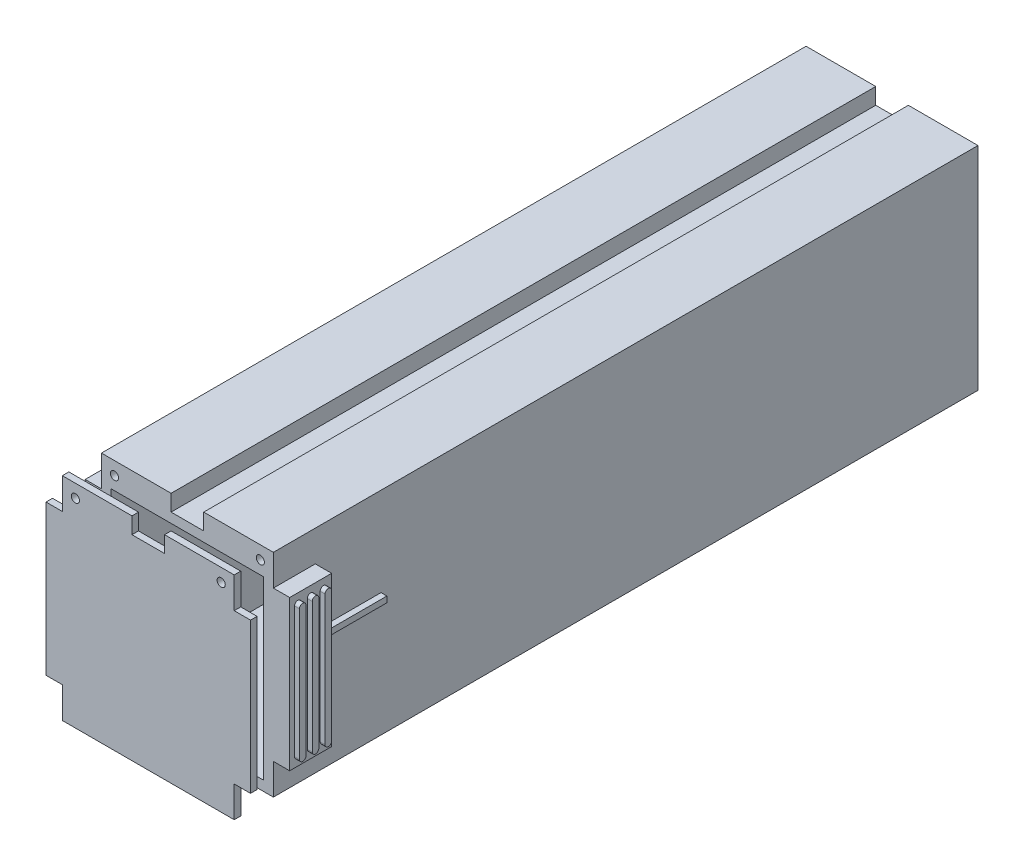
SolidWorks part; units mm, degrees
ref_plane "前视基准面" through (0, 0, 0) normal (0, 0, 1) x (1, 0, 0)
ref_plane "上视基准面" through (0, 0, 0) normal (0, 1, 0) x (1, 0, 0)
ref_plane "右视基准面" through (0, 0, 0) normal (1, 0, 0) x (0, 0, -1)
other "Configuration Table"
sketch "草图1" plane through (0, 0, 0) normal (0, 0, 1) x (1, 0, 0)
  line L1 (0, 0) -> (52.7, 0)
  line L2 (0, 0) -> (0, 65)
  line L3 (0, 65) -> (52.7, 65)
  line L4 (52.7, 0) -> (52.7, 65)
  line L5 (0, 0) -> (52.7, 65) construction
  line L6 (0, 65) -> (52.7, 0) construction
  point P4 (26.35, 32.5)
  dimension "D1" = 52.7
  dimension "D2" = 65
extrude "凸台-拉伸1" add sketch "草图1" along normal blind 216
sketch "草图2" plane through (0, 0, 216) normal (0, 0, 1) x (1, 0, 0)
  line L0 (26.35, 65) -> (26.35, 0) construction
  line L2 (21.35, 65) -> (31.35, 65)
  line L3 (21.35, 65) -> (21.35, 60)
  line L4 (0, 65) -> (0, 0)
  line L5 (0, 0) -> (52.7, 0)
  line L6 (52.7, 0) -> (52.7, 65)
  line L7 (52.7, 65) -> (0, 65)
  line L8 (0, 65) -> (0, 0) construction
  line L9 (0, 0) -> (52.7, 0) construction
  line L10 (52.7, 0) -> (52.7, 65) construction
  line L11 (52.7, 65) -> (0, 65) construction
  line L12 (21.35, 60) -> (31.35, 60)
  line L13 (31.35, 65) -> (31.35, 60)
  line L14 (21.35, 65) -> (31.35, 60) construction
  line L15 (21.35, 60) -> (31.35, 65) construction
  point P10 (26.35, 62.5)
  line M11 (52.7, 65) -> (0, 65)
  dimension "D2" = 5
  dimension "D3" = 10
  dimension "D1" = 0
extrude "切除-拉伸1" cut sketch "草图2" against normal through all contours L3 L12 L0 M11
sketch "草图3" plane through (0, 0, 216) normal (0, 0, 1) x (1, 0, 0)
  line L0 (0, 60) -> (52.7, 60) construction
  line L1 (3, 57) -> (49.7, 57)
  line L2 (49.7, 3) -> (49.7, 57)
  line L3 (3, 3) -> (49.7, 3)
  line L4 (3, 57) -> (3, 3)
  line L5 (31.35, 57) -> (21.35, 57)
  line L8 (31.35, 60) -> (21.35, 60)
  line L9 (21.35, 60) -> (21.35, 65)
  line L10 (21.35, 65) -> (0, 65)
  line L11 (0, 65) -> (0, 0)
  line L12 (0, 0) -> (52.7, 0)
  line L13 (52.7, 0) -> (52.7, 65)
  line L14 (52.7, 65) -> (31.35, 65)
  line L15 (31.35, 65) -> (31.35, 60)
  line L16 (31.35, 60) -> (21.35, 60)
  line L19 (0, 60) -> (0, 0) construction
  line L20 (0, 0) -> (52.7, 0) construction
  line L21 (52.7, 0) -> (52.7, 60) construction
  line L30 (31.35, 65) -> (31.35, 60)
  dimension "D1" = 0
  dimension "D2" = 3
extrude "切除-拉伸2" cut sketch "草图3" against normal offset from surface (211 mm away) 5 contours L1 L4 L3 L2 up to face at (26.35, 47.5, 0)
sketch "草图6" plane through (0, 0, 0) normal (0, 0, -1) x (-1, 0, 0)
  line L0 (-26.35, 60) -> (-26.35, 0) construction
  line L1 (-21.35, 60) -> (-31.35, 60) construction
  line L2 (0, 0) -> (-52.7, 0) construction
  line L3 (-40.6065, 14.2) -> (-11.5971, 14.2) construction
  line L4 (-34.35, 22.2) -> (-18.35, 22.2)
  line L5 (-34.35, 22.2) -> (-34.35, 6.2)
  line L6 (-34.35, 6.2) -> (-18.35, 6.2)
  line L7 (-18.35, 22.2) -> (-18.35, 6.2)
  line L8 (-34.35, 22.2) -> (-18.35, 6.2) construction
  line L9 (-34.35, 6.2) -> (-18.35, 22.2) construction
  line L10 (-39.1, 14.2) -> (-13.6, 14.2) construction
  line L15 (-3, 3) -> (-3, 57)
  line L16 (-49.7, 3) -> (-3, 3)
  line L17 (-49.7, 57) -> (-49.7, 3)
  line L18 (-3, 57) -> (-49.7, 57)
  line L19 (-3, 3) -> (-3, 57) construction
  line L20 (-49.7, 3) -> (-3, 3) construction
  line L21 (-49.7, 57) -> (-49.7, 3) construction
  line L22 (-3, 57) -> (-49.7, 57) construction
  circle A0 centre (-13.6, 14.2) radius 1.75
  circle A1 centre (-39.1, 14.2) radius 1.75
  point P10 (-26.35, 14.2)
  point P17 (-26.35, 14.2)
  dimension "D5" = 3.5
  dimension "D6" = 3.5
  dimension "D1" = 3.2
  dimension "D2" = 16
  dimension "D3" = 0
  dimension "D4" = 16
  dimension "D7" = 25.5
  dimension "D8" = 0
extrude "切除-拉伸3" cut sketch "草图6" against normal offset from surface (5 mm away) 5 up to face at (26.35, 47.5, 0)
sketch "草图7" plane through (0, 0, 216) normal (0, 0, 1) x (1, 0, 0)
  line L0 (52.7, 0) -> (52.7, 65) construction
  line L1 (52.7, 36) -> (54.5, 36)
  line L2 (52.7, 36) -> (52.7, 37.8)
  line L3 (52.7, 37.8) -> (54.5, 37.8)
  line L4 (54.5, 36) -> (54.5, 37.8)
  line L5 (52.7, 36) -> (54.5, 37.8) construction
  line L6 (52.7, 37.8) -> (54.5, 36) construction
  line L7 (52.7, 65) -> (31.35, 65) construction
  point P4 (53.6, 36.9)
  dimension "D1" = 29
  dimension "D2" = 1.8
  dimension "D3" = 1.8
extrude "凸台-拉伸2" add sketch "草图7" against normal blind 33
sketch "草图9" plane through (0, 0, 0) normal (-1, 0, 0) x (0, 0, 1)
  line L0 (218, 32.5) -> (0, 32.5) construction
  line L3 (216, 65) -> (216, 0) construction
  line L4 (216, 55.5) -> (203.15, 55.5)
  line L5 (216, 55.5) -> (216, 9.5)
  line L6 (216, 9.5) -> (203.15, 9.5)
  line L7 (203.15, 55.5) -> (203.15, 9.5)
  line L8 (216, 55.5) -> (203.15, 9.5) construction
  line L9 (216, 9.5) -> (203.15, 55.5) construction
  point P5 (209.575, 32.5)
  point P9 (0, 0)
  dimension "D1" = 12.85
  dimension "D2" = 46
extrude "凸台-拉伸3" add sketch "草图9" along normal blind 5
sketch "草图10" plane through (52.7, 0, 0) normal (1, 0, 0) x (0, 0, -1)
  line L4 (-203.15, 55.5) -> (-216, 55.5)
  line L5 (-203.15, 9.5) -> (-203.15, 55.5)
  line L6 (-216, 9.5) -> (-203.15, 9.5)
  line L7 (-216, 55.5) -> (-216, 9.5)
  line L8 (-203.15, 55.5) -> (-216, 55.5)
  line L9 (-203.15, 9.5) -> (-203.15, 55.5)
  line L10 (-216, 9.5) -> (-203.15, 9.5)
  line L11 (-216, 55.5) -> (-216, 9.5)
  dimension "D1" = 0
extrude "凸台-拉伸4" add sketch "草图10" along normal blind 5
sketch "草图11" plane through (57.7, 0, 0) normal (1, 0, 0) x (0, 0, -1)
  line L0 (-216, 32.5) -> (-203.15, 32.5) construction
  line L1 (-216, 55.5) -> (-216, 9.5) construction
  line L2 (-203.15, 9.5) -> (-203.15, 55.5) construction
  line L3 (-213.5, 12.5) -> (-213.5, 52.5) construction
  line L4 (-214.5, 12.5) -> (-214.5, 52.5)
  line L5 (-212.5, 12.5) -> (-212.5, 52.5)
  line L6 (-209.575, 12.5) -> (-209.575, 52.5) construction
  line L7 (-210.575, 12.5) -> (-210.575, 52.5)
  line L8 (-208.575, 12.5) -> (-208.575, 52.5)
  line L9 (-205.65, 12.5) -> (-205.65, 52.5) construction
  line L10 (-206.65, 12.5) -> (-206.65, 52.5)
  line L11 (-204.65, 12.5) -> (-204.65, 52.5)
  line L12 (-203.15, 37.8) -> (-203.15, 55.5) construction
  arc A0 (-214.5, 12.5) -> (-212.5, 12.5) centre (-213.5, 12.5) ccw
  arc A1 (-212.5, 52.5) -> (-214.5, 52.5) centre (-213.5, 52.5) ccw
  arc A2 (-210.575, 12.5) -> (-208.575, 12.5) centre (-209.575, 12.5) ccw
  arc A3 (-208.575, 52.5) -> (-210.575, 52.5) centre (-209.575, 52.5) ccw
  arc A4 (-206.65, 12.5) -> (-204.65, 12.5) centre (-205.65, 12.5) ccw
  arc A5 (-204.65, 52.5) -> (-206.65, 52.5) centre (-205.65, 52.5) ccw
  point P8 (-213.5, 32.5)
  point P14 (-209.575, 32.5)
  point P21 (-205.65, 32.5)
  dimension "D1" = 40
  dimension "D2" = 2
  dimension "D3" = 2.5
  dimension "D4" = 2.5
extrude "凸台-拉伸5" add sketch "草图11" along normal blind 1.5
sketch "草图12" plane through (-5, 0, 0) normal (-1, 0, 0) x (0, 0, 1)
  line L2 (214.5, 12.5) -> (214.5, 52.5)
  line L3 (212.5, 52.5) -> (212.5, 12.5)
  line L4 (214.5, 12.5) -> (214.5, 52.5)
  line L5 (212.5, 52.5) -> (212.5, 12.5)
  line L6 (206.65, 12.5) -> (206.65, 52.5)
  line L7 (204.65, 52.5) -> (204.65, 12.5)
  line L8 (206.65, 12.5) -> (206.65, 52.5)
  line L9 (204.65, 52.5) -> (204.65, 12.5)
  line L10 (210.575, 12.5) -> (210.575, 52.5)
  line L11 (208.575, 52.5) -> (208.575, 12.5)
  line L12 (210.575, 12.5) -> (210.575, 52.5)
  line L13 (208.575, 52.5) -> (208.575, 12.5)
  arc A2 (214.5, 52.5) -> (212.5, 52.5) centre (213.5, 52.5) ccw
  arc A3 (212.5, 12.5) -> (214.5, 12.5) centre (213.5, 12.5) ccw
  arc A4 (214.5, 52.5) -> (212.5, 52.5) centre (213.5, 52.5) ccw
  arc A5 (212.5, 12.5) -> (214.5, 12.5) centre (213.5, 12.5) ccw
  arc A6 (206.65, 52.5) -> (204.65, 52.5) centre (205.65, 52.5) ccw
  arc A7 (204.65, 12.5) -> (206.65, 12.5) centre (205.65, 12.5) ccw
  arc A8 (206.65, 52.5) -> (204.65, 52.5) centre (205.65, 52.5) ccw
  arc A9 (204.65, 12.5) -> (206.65, 12.5) centre (205.65, 12.5) ccw
  arc A10 (210.575, 52.5) -> (208.575, 52.5) centre (209.575, 52.5) ccw
  arc A11 (208.575, 12.5) -> (210.575, 12.5) centre (209.575, 12.5) ccw
  arc A12 (210.575, 52.5) -> (208.575, 52.5) centre (209.575, 52.5) ccw
  arc A13 (208.575, 12.5) -> (210.575, 12.5) centre (209.575, 12.5) ccw
  dimension "D1" = 0
  dimension "D2" = 0
  dimension "D3" = 0
extrude "凸台-拉伸6" add sketch "草图12" along normal blind 1.5
ref_plane "基准面1" through (0, 0, 226) normal (0, 0, 1) x (1, 0, 0)
sketch "草图14" plane through (0, 0, 226) normal (0, 0, 1) x (1, 0, 0)
  line L4 (3, 57) -> (3, 3)
  line L5 (3, 3) -> (49.7, 3)
  line L6 (49.7, 3) -> (49.7, 57)
  line L7 (49.7, 57) -> (3, 57)
  line L8 (3, 57) -> (3, 3) construction
  line L9 (3, 3) -> (49.7, 3) construction
  line L10 (49.7, 3) -> (49.7, 57) construction
  line L11 (49.7, 57) -> (3, 57) construction
  line L16 (57.7, 55.5) -> (52.7, 55.5)
  line L17 (52.7, 55.5) -> (52.7, 65)
  line L18 (52.7, 65) -> (31.35, 65)
  line L19 (31.35, 65) -> (31.35, 60)
  line L20 (31.35, 60) -> (21.35, 60)
  line L21 (21.35, 60) -> (21.35, 65)
  line L22 (21.35, 65) -> (0, 65)
  line L23 (0, 65) -> (0, 55.5)
  line L24 (0, 55.5) -> (-5, 55.5)
  line L25 (-5, 55.5) -> (-5, 9.5)
  line L26 (-5, 9.5) -> (0, 9.5)
  line L27 (0, 9.5) -> (0, 0)
  line L28 (0, 0) -> (52.7, 0)
  line L29 (52.7, 0) -> (52.7, 9.5)
  line L30 (52.7, 9.5) -> (57.7, 9.5)
  line L31 (57.7, 9.5) -> (57.7, 55.5)
  line L32 (57.7, 55.5) -> (52.7, 55.5)
  line L33 (52.7, 55.5) -> (52.7, 65)
  line L34 (52.7, 65) -> (31.35, 65)
  line L35 (31.35, 65) -> (31.35, 60)
  line L36 (31.35, 60) -> (21.35, 60)
  line L37 (21.35, 60) -> (21.35, 65)
  line L38 (21.35, 65) -> (0, 65)
  line L39 (0, 65) -> (0, 55.5)
  line L40 (0, 55.5) -> (-5, 55.5)
  line L41 (-5, 55.5) -> (-5, 9.5)
  line L42 (-5, 9.5) -> (0, 9.5)
  line L43 (0, 9.5) -> (0, 0)
  line L44 (0, 0) -> (52.7, 0)
  line L45 (52.7, 0) -> (52.7, 9.5)
  line L46 (52.7, 9.5) -> (57.7, 9.5)
  line L47 (57.7, 9.5) -> (57.7, 55.5)
  dimension "D1" = 0
  dimension "D2" = 0
extrude "凸台-拉伸7" add sketch "草图14" along normal blind 2 separate body
sketch "草图15" plane through (0, 0, 228) normal (0, 0, 1) x (1, 0, 0)
  line L0 (21.35, 65) -> (0, 65) construction
  line L1 (0, 65) -> (0, 55.5) construction
  line L2 (52.7, 65) -> (31.35, 65) construction
  line L3 (52.7, 55.5) -> (52.7, 65) construction
  circle A0 centre (4, 61) radius 1.25
  circle A1 centre (48.7, 61) radius 1.25
  point P12 (63.9114, 70.1382)
  dimension "D1" = 2.5
  dimension "D2" = 2.5
  dimension "D3" = 4
  dimension "D4" = 4
  dimension "D5" = 4
  dimension "D6" = 4
extrude "切除-拉伸4" cut sketch "草图15" against normal blind 20
